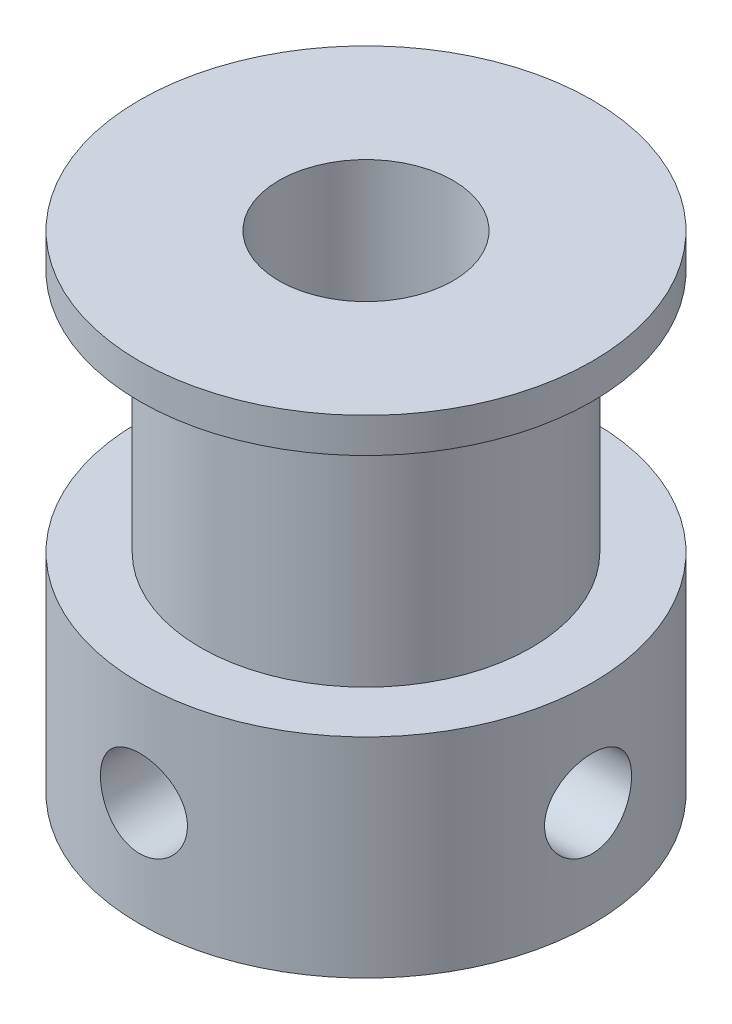
SolidWorks part; units mm, degrees
material "6063-O"
ref_plane "前视基准面" through (0, 0, 0) normal (0, 0, 1) x (1, 0, 0)
ref_plane "上视基准面" through (0, 0, 0) normal (0, 1, 0) x (1, 0, 0)
ref_plane "右视基准面" through (0, 0, 0) normal (1, 0, 0) x (0, 0, -1)
sketch "草图1" plane through (0, 0, 0) normal (0, 0, 1) x (1, 0, 0)
  line L0 (0, 0) -> (0, 14) construction
  line L1 (2.5, 0) -> (6.5, 0)
  line L2 (6.5, 0) -> (6.5, 6)
  line L3 (6.5, 6) -> (4.75, 6)
  line L4 (4.75, 6) -> (4.75, 13)
  line L5 (4.75, 13) -> (6.5, 13)
  line L6 (6.5, 13) -> (6.5, 14)
  line L7 (6.5, 14) -> (2.5, 14)
  line L8 (2.5, 14) -> (2.5, 0)
  dimension "D1" = 5
  dimension "D2" = 13
  dimension "D3" = 14
  dimension "D4" = 7
  dimension "D5" = 9.5
  dimension "D6" = 1
revolve "旋转1" add sketch "草图1" angle 360 about L0
hole_wizard "M3 螺纹孔1" positions "草图2" profile "草图3" tap size "M3" standard "GB"
sketch "草图2" plane through (0, 0, 0) normal (0, 0, 1) x (1, 0, 0)
  point P0 (0, 3)
  dimension "D1" = 3
sketch "草图3" plane through (0, 3, 0) normal (1, 0, 0) x (0, 1, 0)
  line L0 (0, 0) -> (0, 6.5)
  line L1 (0, 6.5) -> (1.25, 6.5)
  line L2 (1.25, 6.5) -> (1.25, 0.275)
  line L3 (1.25, 0.275) -> (1.525, 0)
  line L5 (1.525, 0) -> (0, 0)
  line L6 (-1.25, 0.275) -> (-1.525, 0) construction
  line L11 (0, -6.35) -> (0, 107.95) construction
  dimension "通孔螺纹孔钻头直径" = 2.5
  dimension "通孔螺纹孔钻头深度" = 6.5
  dimension "近端锥形沉头孔直径" = 3.05
  dimension "近端锥形沉头孔角度" = 90
cosmetic thread "孔螺蚊线1" parameters "D2"=3
hole_wizard "M3 螺纹孔2" positions "草图4" profile "草图5" tap size "M3" standard "GB"
sketch "草图4" plane through (0, 0, 0) normal (1, 0, 0) x (0, 0, -1)
  point P0 (0, 3)
  dimension "D1" = 3
sketch "草图5" plane through (0, 3, 0) normal (0, 1, 0) x (0, 0, 1)
  line L0 (0, 0) -> (0, 6.5)
  line L1 (0, 6.5) -> (1.25, 6.5)
  line L2 (1.25, 6.5) -> (1.25, 0.275)
  line L3 (1.25, 0.275) -> (1.525, 0)
  line L5 (1.525, 0) -> (0, 0)
  line L6 (-1.25, 0.275) -> (-1.525, 0) construction
  line L11 (0, -6.35) -> (0, 107.95) construction
  dimension "通孔螺纹孔钻头直径" = 2.5
  dimension "通孔螺纹孔钻头深度" = 6.5
  dimension "近端锥形沉头孔直径" = 3.05
  dimension "近端锥形沉头孔角度" = 90
cosmetic thread "孔螺蚊线2" parameters "D2"=3
